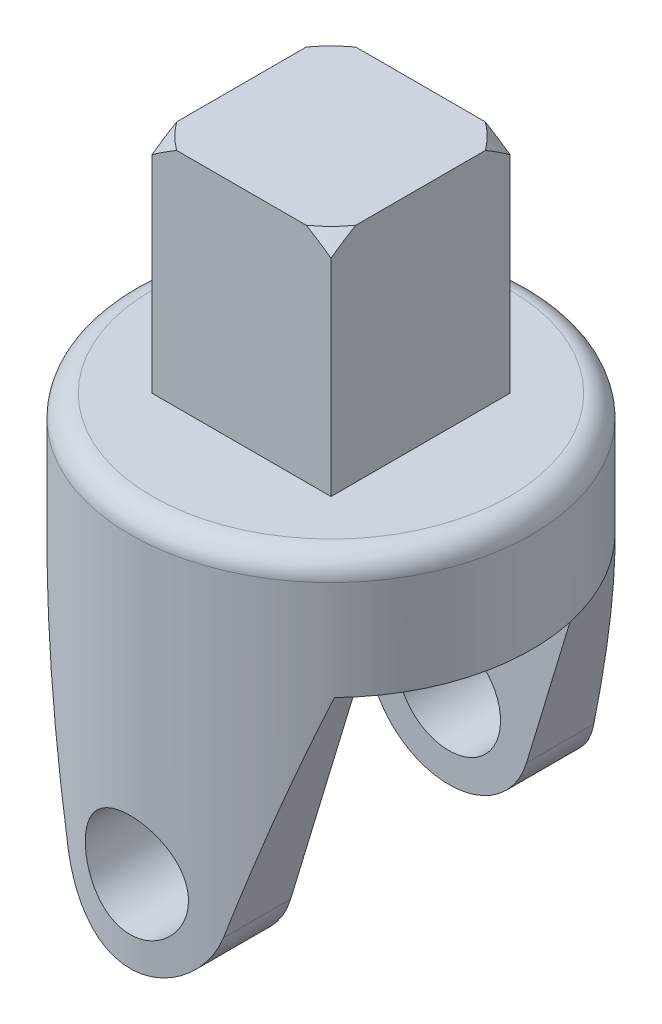
SolidWorks part; units mm, degrees
material "AISI Type A2 Tool Steel"
ref_plane "FRONT" through (0, 0, 0) normal (0, 0, 1) x (1, 0, 0)
ref_plane "TOP" through (0, 0, 0) normal (0, 1, 0) x (1, 0, 0)
ref_plane "RIGHT" through (0, 0, 0) normal (1, 0, 0) x (0, 0, -1)
sketch "Base" plane through (0, 0, 0) normal (0, 1, 0) x (1, 0, 0)
  circle A0 centre (0, 0) radius 6.9215
  dimension "BDia" = 13.843
extrude "Base-Extrude" add sketch "Base" along normal blind 13.716 separate body
sketch "MaleDrive" plane through (0, 13.716, 0) normal (0, 1, 0) x (1, 0, 0)
  circle A0 centre (0, 0) radius 6.0579
  dimension "ShaftDia" = 12.1158
extrude "Drive-Extrude" add sketch "MaleDrive" along normal offset from surface (7.6708 mm away) 21.3868 up to plane "TOP"
sketch "Drive-ChamCut" plane through (0, 0, 0) normal (0, 0, 1) x (1, 0, 0)
  line L0 (0, 0) -> (0, 21.3868) construction
  line L1 (6.0579, 21.3868) -> (-6.0579, 21.3868) construction
  line L2 (-3.81, 21.3868) -> (-5.4229, 19.7739)
  line L4 (-5.4229, 19.7739) -> (-5.4229, 21.3868)
  line L5 (-5.4229, 21.3868) -> (-3.81, 21.3868)
  line L6 (6.0579, 21.3868) -> (-6.0579, 21.3868) construction
  dimension "D1" = 45
  dimension "RCD" = 7.62
revolve "DriveEnd-Chamfer" cut sketch "Drive-ChamCut" angle 360 about L0
sketch "SQDrive-Sk" plane through (0, 21.3868, 0) normal (0, 1, 0) x (-1, 0, 0)
  line L1 (-3.0861, -3.0861) -> (3.0861, -3.0861)
  line L2 (-3.0861, -3.0861) -> (-3.0861, 3.0861)
  line L3 (-3.0861, 3.0861) -> (3.0861, 3.0861)
  line L4 (3.0861, -3.0861) -> (3.0861, 3.0861)
  line L5 (-3.0861, -3.0861) -> (3.0861, 3.0861) construction
  line L6 (-3.0861, 3.0861) -> (3.0861, -3.0861) construction
  point P0 (0, 0)
  dimension "SAF" = 6.1722
extrude "Drive-SQCut" cut sketch "SQDrive-Sk" against normal blind 7.6708 flip side to cut
fillet "Base-Fillet_Top" radius 0.762 1 edges at (0, 13.716, 6.9215)
sketch "Profile1-CutSk" plane through (0, 0, 0) normal (1, 0, 0) x (0, 0, -1)
  line L0 (-6.9215, 0) -> (6.9215, 0) construction
  line L1 (-4.064, 9.525) -> (4.064, 9.525)
  line L2 (-4.064, 9.525) -> (-4.064, 0)
  line L3 (-4.064, 0) -> (4.064, 0)
  line L4 (4.064, 9.525) -> (4.064, 0)
  line L5 (6.1595, 13.716) -> (-6.1595, 13.716) construction
  dimension "DimA" = 8.128
  dimension "DimF" = 4.191
extrude "Profile1-Cut" cut sketch "Profile1-CutSk" against normal through all and the other way through all
sketch "Profile2-CutSk" plane through (0, 0, 0) normal (0, 0, 1) x (1, 0, 0)
  line L0 (4.953, 9.525) -> (2.6745, 1.9857)
  line L1 (-6.9215, 12.954) -> (-6.9215, 9.525) construction
  line L2 (2.6745, 1.9857) -> (-2.6745, 1.9857) construction
  line L3 (-2.6745, 1.9857) -> (-4.953, 9.525)
  line L4 (6.9215, 9.525) -> (6.9215, 12.954) construction
  line L5 (4.953, 9.525) -> (-4.953, 9.525) construction
  line L6 (0, 9.525) -> (0, 0) construction
  line L7 (0, 9.525) -> (0, 0) construction
  line L8 (4.953, 9.525) -> (6.9215, 9.525)
  line L9 (-4.953, 9.525) -> (-6.9215, 9.525)
  line L10 (-6.9215, 9.525) -> (-5.6028, 9.525) construction
  arc A0 (-2.6745, 1.9857) -> (2.6745, 1.9857) centre (0, 2.794) ccw
  dimension "0" = 2.794
  dimension "DimG" = 9.906
extrude "Profile2-Cut" cut sketch "Profile2-CutSk" against normal through all and the other way through all
sketch "Pin-CutSk" plane through (0, 0, 0) normal (0, 0, 1) x (1, 0, 0)
  circle A0 centre (0, 2.794) radius 1.778
  dimension "Pin_Dia" = 3.556
extrude "Pin-Cut" cut sketch "Pin-CutSk" against normal through all and the other way through all
equation "\"D1@Drive-SQCut\" = \"OAL@Drive-Extrude\" - \"BL@Base-Extrude\""
